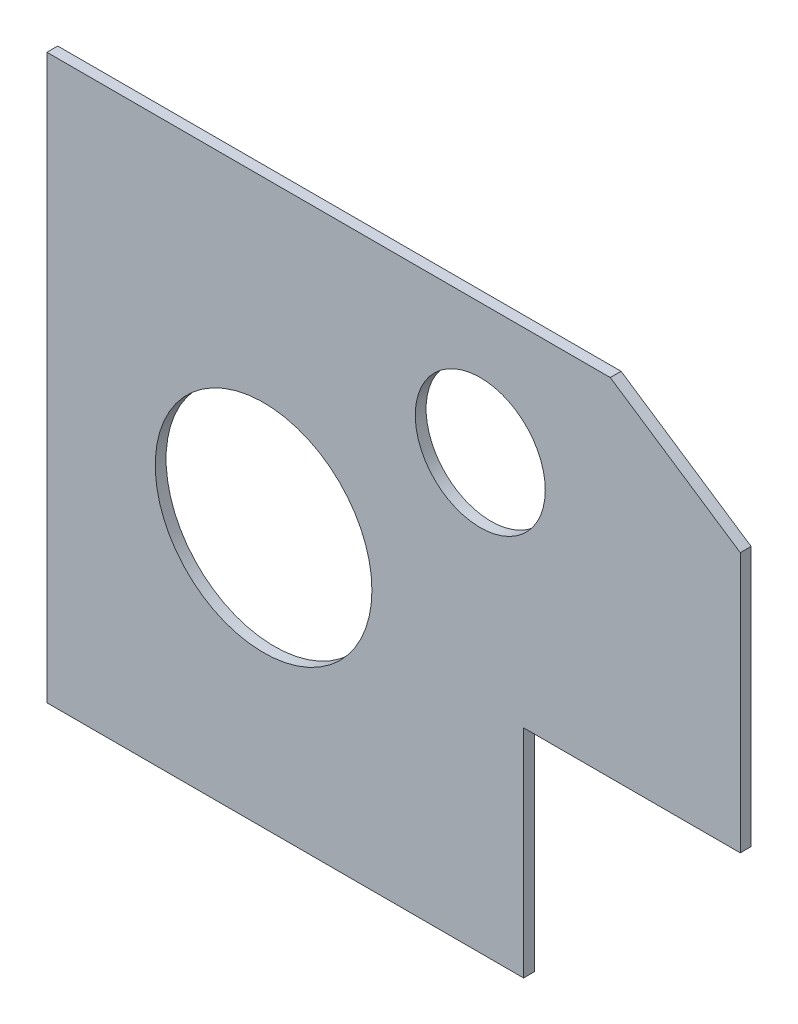
SolidWorks part; units mm, degrees
ref_plane "Front Plane" through (0, 0, 0) normal (0, 0, 1) x (1, 0, 0)
ref_plane "Top Plane" through (0, 0, 0) normal (0, 1, 0) x (1, 0, 0)
ref_plane "Right Plane" through (0, 0, 0) normal (1, 0, 0) x (0, 0, -1)
sketch "Sketch2" plane through (0, 0, 0) normal (0, 0, 1) x (1, 0, 0)
  line L1 (0, 0) -> (203.2, 0)
  line L2 (0, 0) -> (0, 165.1)
  line L3 (0, 165.1) -> (203.2, 165.1)
  line L4 (203.2, 0) -> (203.2, 165.1)
  dimension "D1" = 203.2
  dimension "D2" = 165.1
extrude "Boss-Extrude1" add sketch "Sketch2" along normal blind 3.175
sketch "Sketch6" plane through (0, 0, 0) normal (0, 0, -1) x (-1, 0, 0)
  line L1 (-203.2, 0) -> (-139.7, 0)
  line L2 (-203.2, 0) -> (-203.2, 63.5)
  line L3 (-203.2, 63.5) -> (-139.7, 63.5)
  line L4 (-139.7, 0) -> (-139.7, 63.5)
  dimension "D1" = 63.5
  dimension "D2" = 63.5
extrude "Cut-Extrude1" cut sketch "Sketch6" against normal up to next
sketch "Sketch7" plane through (0, 0, 3.175) normal (0, 0, 1) x (1, 0, 0)
  line L0 (165.1, 165.1) -> (203.2, 139.7)
  line L1 (203.2, 165.1) -> (0, 165.1) construction
  line L2 (203.2, 63.5) -> (203.2, 165.1) construction
  line L3 (0, 0) -> (139.7, 0) construction
  dimension "D1" = 165.1
  dimension "D2" = 139.7
extrude "Cut-Extrude3" cut sketch "Sketch7" against normal through all and the other way through all
sketch "Sketch13" plane through (0, 0, 3.175) normal (0, 0, 1) x (1, 0, 0)
  line L0 (0, 165.1) -> (0, 0) construction
  line L2 (165.1, 165.1) -> (0, 165.1) construction
  circle A0 centre (127, 127) radius 19.05
  circle A1 centre (63.5, 76.2) radius 31.75
  point P7 (0, 0)
  point P9 (47.2034, 165.1)
  dimension "D1" = 38.1
  dimension "D2" = 63.5
  dimension "D3" = 63.5
  dimension "D4" = 76.2
  dimension "D5" = 127
  dimension "D6" = 38.1
extrude "Cut-Extrude4" cut sketch "Sketch13" against normal through all
